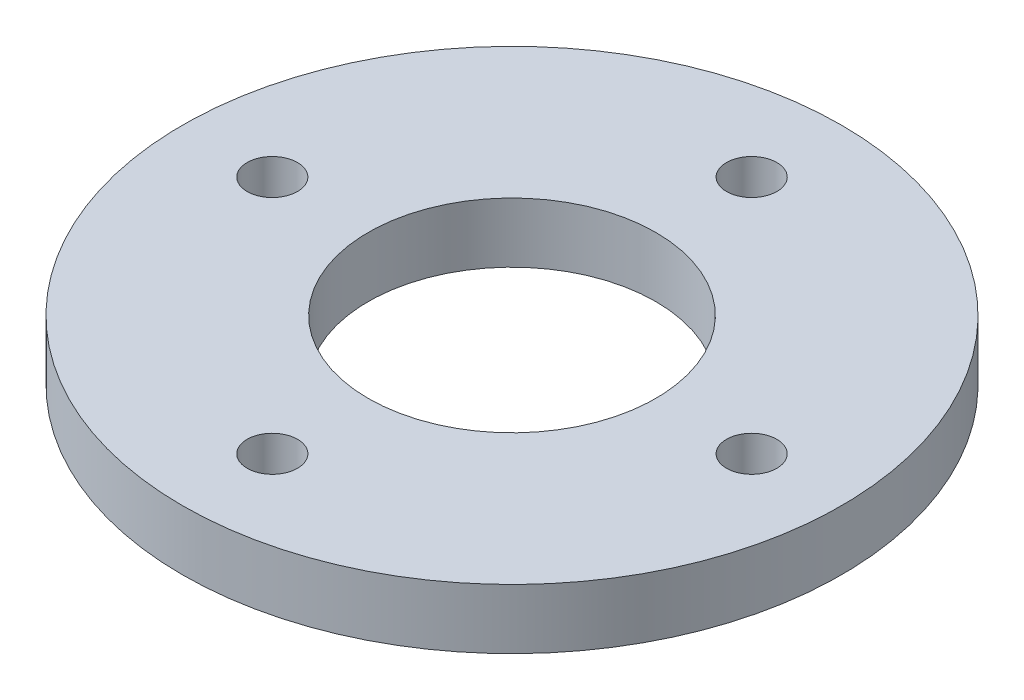
SolidWorks part; units mm, degrees
ref_plane "Front Plane" through (0, 0, 0) normal (0, 0, 1) x (1, 0, 0)
ref_plane "Top Plane" through (0, 0, 0) normal (0, 1, 0) x (1, 0, 0)
ref_plane "Right Plane" through (0, 0, 0) normal (1, 0, 0) x (0, 0, -1)
sketch "Sketch1" plane through (0, 0, 0) normal (0, 1, 0) x (1, 0, 0)
  circle A0 centre (0, 0) radius 12
  circle A1 centre (0, 0) radius 27.5
  dimension "D1" = 24
  dimension "D2" = 55
extrude "Boss-Extrude1" add sketch "Sketch1" along normal blind 5
sketch "Sketch2" plane through (0, 5, 0) normal (0, 1, 0) x (1, 0, 0)
  line L0 (0, 27.7678) -> (0, 0.2678) construction
  line L1 (-27.5, 0) -> (26.9593, 0) construction
  circle A1 centre (0, 20) radius 2.1
  circle A2 centre (0, -20) radius 2.1
  circle A3 centre (20, 0) radius 2.1
  circle A4 centre (-20, 0) radius 2.1
  circle A5 centre (0, 0) radius 27.5 construction
  dimension "D1" = 4.2
  dimension "D2" = 4.2
  dimension "D3" = 4.2
  dimension "D4" = 4.2
  dimension "D5" = 20
  dimension "D6" = 20
  dimension "D7" = 20
  dimension "D8" = 20
extrude "Cut-Extrude1" cut sketch "Sketch2" against normal blind 5
